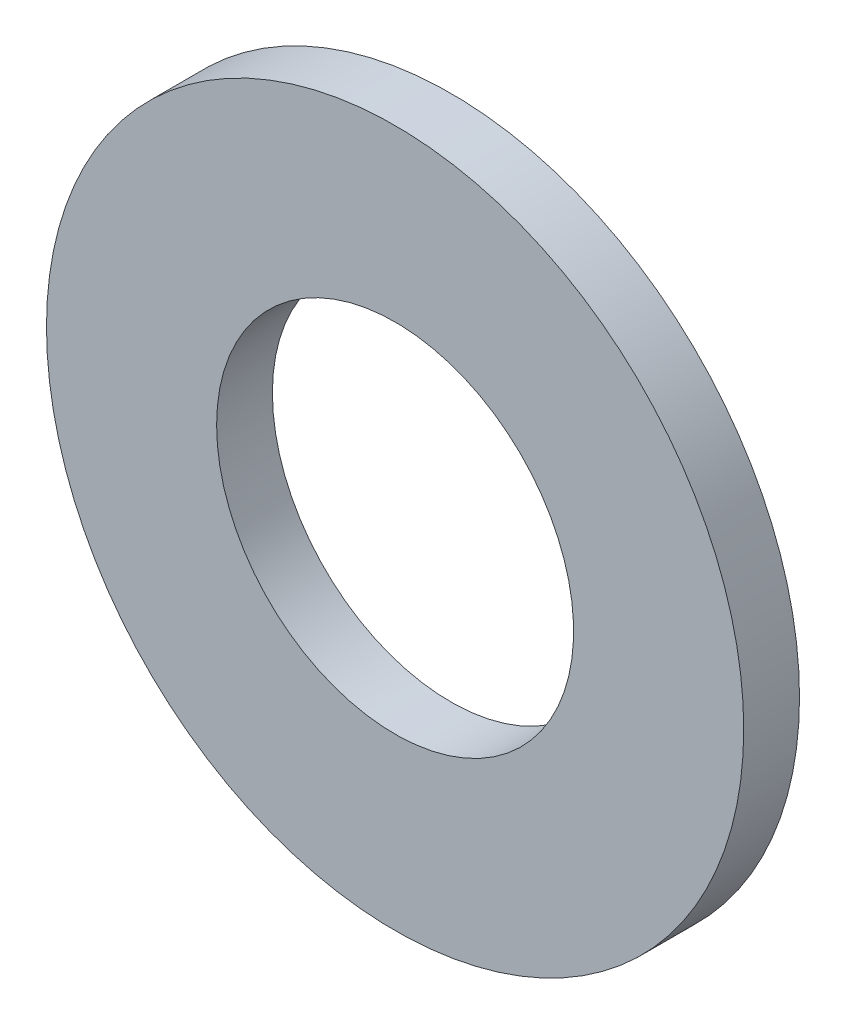
SolidWorks part; units mm, degrees
ref_plane "Plan de face" through (0, 0, 0) normal (0, 0, 1) x (1, 0, 0)
ref_plane "Plan de dessus" through (0, 0, 0) normal (0, 1, 0) x (1, 0, 0)
ref_plane "Plan de droite" through (0, 0, 0) normal (1, 0, 0) x (0, 0, -1)
sketch "Esquisse1" plane through (0, 0, 0) normal (0, 0, 1) x (1, 0, 0)
  circle A0 centre (0, 0) radius 3.2
  circle A1 centre (0, 0) radius 6.25
extrude "Boss.-Extru.1" add sketch "Esquisse1" along normal blind 1
hole_wizard "Dégagement M42" positions "Esquisse4" profile "Esquisse5"
sketch "Esquisse4" plane through (7.8248, 79.5071, 44.6) normal (0, 0, 1) x (0.8197, -0.5728, 0)
  point P0 (11.89, -41.884)
  point P3 (92.8027, -46.1429)
  point P6 (83.8294, -80.9061)
sketch "Esquisse5" plane through (-10.5871, 32.7401, 44.6) normal (1, 0, 0) x (0, -1, 0)
  line L0 (0, 0) -> (0, 361.6937)
  line L1 (0, 361.6937) -> (2.25, 361.6937)
  line L2 (2.25, 361.6937) -> (2.25, 0)
  line L3 (2.25, 0) -> (0, 0)
  line L4 (0, -6.35) -> (0, 107.95) construction
  dimension "Diamètre du perçage jusqu'au prochain" = 4.5
  dimension "Profondeur du perçage jusqu'au prochain" = 361.6937
